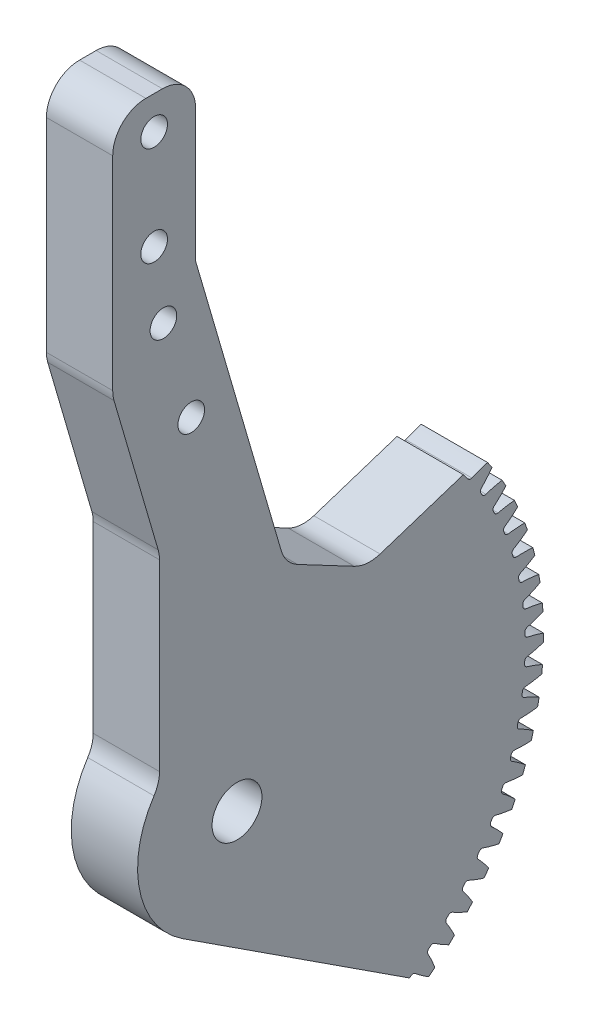
SolidWorks part; units mm, degrees
material "Delrin 2700 NC010, Low Viscosity Acetal Copolymer (SS)"
ref_plane "Front Plane" through (0, 0, 0) normal (0, 0, 1) x (1, 0, 0)
ref_plane "Top Plane" through (0, 0, 0) normal (0, 1, 0) x (1, 0, 0)
ref_plane "Right Plane" through (0, 0, 0) normal (1, 0, 0) x (0, 0, -1)
ref_plane "Plane1" through (-6.35, 0, 0) normal (-1, 0, 0) x (0, -1, 0)
sketch "Sketch1" plane through (-6.35, 0, 0) normal (-1, 0, 0) x (0, -1, 0)
  line L0 (-81.6791, 23.8125) -> (-120.65, 23.8125)
  line L1 (-127, 17.4625) -> (-127, 14.2875)
  line L2 (-120.65, 7.9375) -> (-95.25, 7.9375)
  line L3 (-95.25, 7.9375) -> (-38.9677, -8.4782)
  line L4 (-35.1315, -11.6072) -> (-29.3819, -22.4868)
  line L5 (-28.9579, -27.4191) -> (-34.0808, -43.1589)
  line L6 (44.0898, -32.8675) -> (15.9715, 10.3834)
  line L7 (-13.9936, 14.8476) -> (-49.1281, 14.8476)
  line L8 (-50.9061, 15.1016) -> (-79.9011, 23.5585)
  arc A0 (-120.65, 23.8125) -> (-127, 17.4625) centre (-120.65, 17.4625) ccw
  arc A1 (-127, 14.2875) -> (-120.65, 7.9375) centre (-120.65, 14.2875) ccw
  arc A2 (-38.9677, -8.4782) -> (-35.1315, -11.6072) centre (-40.7457, -14.5742) cw
  arc A3 (-29.3819, -22.4868) -> (-28.9579, -27.4191) centre (-34.9961, -25.4538) cw
  arc A4 (-34.0808, -43.1589) -> (-32.8888, -46.7381) centre (-31.0617, -44.1415) ccw
  arc A5 (-32.8888, -46.7381) -> (43.8649, -36.6333) centre (0, 0) ccw
  arc A6 (43.8649, -36.6333) -> (44.0898, -32.8675) centre (41.4279, -34.5981) ccw
  arc A7 (15.9715, 10.3834) -> (-10.4952, 15.8982) centre (0, 0) ccw
  arc A8 (-10.4952, 15.8982) -> (-13.9936, 14.8476) centre (-13.9936, 21.1976) cw
  arc A9 (-49.1281, 14.8476) -> (-50.9061, 15.1016) centre (-49.1281, 21.1976) cw
  arc A10 (-79.9011, 23.5585) -> (-81.6791, 23.8125) centre (-81.6791, 17.4625) ccw
  circle A11 centre (0, 0) radius 4.7752
extrude "Boss-Extrude1" add sketch "Sketch1" against normal blind 12.7
sketch "Sketch4" plane through (-6.35, 0, 0) normal (-1, 0, 0) x (0, 0, 1)
  line L0 (-43.1589, 34.0808) -> (-48.5319, 35.8296)
  line L1 (-32.8675, -44.0898) -> (-37.6049, -47.1697)
  line L2 (-32.8675, -44.0898) -> (10.3834, -15.9715) construction
  line L3 (-27.4191, 28.9579) -> (-43.1589, 34.0808) construction
  arc A1 (-36.6333, -43.8649) -> (-32.8675, -44.0898) centre (-34.5981, -41.4279) ccw construction
  arc A2 (-49.3346, 34.716) -> (-38.6685, -46.3018) centre (0, 0) ccw
  arc A3 (-48.5319, 35.8296) -> (-37.6049, -47.1697) centre (0, 0) ccw
  arc A4 (-46.7381, 32.8888) -> (-36.6333, -43.8649) centre (0, 0) ccw construction
  arc A5 (-43.1589, 34.0808) -> (-46.7381, 32.8888) centre (-44.1415, 31.0617) ccw construction
  arc A6 (-36.6333, -43.8649) -> (-32.8675, -44.0898) centre (-34.5981, -41.4279) ccw
  arc A7 (-46.7381, 32.8888) -> (-36.6333, -43.8649) centre (0, 0) ccw
  arc A8 (-43.1589, 34.0808) -> (-46.7381, 32.8888) centre (-44.1415, 31.0617) ccw
  dimension "D1" = 3.175
extrude "Boss-Extrude2" add sketch "Sketch4" against normal up to surface (12.7 mm away) up to face at (6.35, 0, -4.7752)
sketch "Sketch3" plane through (-6.35, 0, 0) normal (-1, 0, 0) x (0, 0, 1)
  line L0 (-27.4191, 28.9579) -> (-48.5319, 35.8296) construction
  line L1 (-37.6049, -47.1697) -> (10.3834, -15.9715) construction
  line L2 (-43.3632, 34.1473) -> (-48.5319, 35.8296)
  line L3 (-37.6049, -47.1697) -> (-33.0476, -44.2069)
  arc A117 (-33.3583, -43.973) -> (-33.0476, -44.2069) centre (0, 0) ccw
  arc A118 (-33.3583, -43.973) -> (-34.1326, -43.9889) centre (-33.7354, -44.47) ccw
  arc A119 (-36.7261, -45.8398) -> (-34.1326, -43.9889) centre (-48.5698, -26.5018) ccw
  arc A120 (-36.5809, -41.9749) -> (-37.8969, -44.8767) centre (-16.6379, -52.7688) ccw
  arc A121 (-36.5809, -41.9749) -> (-36.7146, -41.2121) centre (-37.1296, -41.678) ccw
  arc A122 (-37.0639, -40.8983) -> (-36.7146, -41.2121) centre (0, 0) ccw
  arc A123 (-37.0639, -40.8983) -> (-37.8366, -40.8467) centre (-37.4828, -41.3606) ccw
  arc A124 (-40.5815, -42.4645) -> (-37.8366, -40.8467) centre (-50.6947, -22.1679) ccw
  arc A125 (-40.1, -38.627) -> (-41.664, -41.403) centre (-21.1737, -51.1179) ccw
  arc A126 (-40.1, -38.627) -> (-40.1667, -37.8554) centre (-40.6208, -38.2833) ccw
  arc A127 (-40.4874, -37.5123) -> (-40.1667, -37.8554) centre (0, 0) ccw
  arc A128 (-40.4874, -37.5123) -> (-41.2526, -37.3936) centre (-40.945, -37.9363) ccw
  arc A129 (-44.1281, -38.766) -> (-41.2526, -37.3936) centre (-52.4339, -17.6652) ccw
  arc A130 (-43.314, -34.985) -> (-45.1139, -37.6142) centre (-25.5484, -49.078) ccw
  arc A131 (-43.314, -34.985) -> (-43.3132, -34.2106) centre (-43.8028, -34.5973) ccw
  arc A132 (-43.6027, -33.8409) -> (-43.3132, -34.2106) centre (0, 0) ccw
  arc A133 (-43.6027, -33.8409) -> (-44.3547, -33.6559) centre (-44.0956, -34.2234) ccw
  arc A134 (-47.3389, -34.7724) -> (-44.3547, -33.6559) centre (-53.774, -13.028) ccw
  arc A135 (-46.1983, -31.0769) -> (-48.2205, -33.5391) centre (-29.7286, -46.6645) ccw
  arc A136 (-46.1983, -31.0769) -> (-46.13, -30.3054) centre (-46.6515, -30.648) ccw
  arc A137 (-46.3862, -29.9119) -> (-46.13, -30.3054) centre (0, 0) ccw
  arc A138 (-46.3862, -29.9119) -> (-47.1192, -29.662) centre (-46.9105, -30.25) ccw
  arc A139 (-50.1894, -30.5143) -> (-47.1192, -29.662) centre (-54.7048, -8.2918) ccw
  arc A140 (-48.7311, -26.9321) -> (-50.9602, -29.2088) centre (-33.6825, -43.896) ccw
  arc A141 (-48.7311, -26.9321) -> (-48.5958, -26.1696) centre (-49.1451, -26.4654) ccw
  arc A142 (-48.8167, -25.7552) -> (-48.5958, -26.1696) centre (0, 0) ccw
  arc A143 (-48.8167, -25.7552) -> (-49.5251, -25.4424) centre (-49.3685, -26.0463) ccw
  arc A144 (-52.6579, -26.0239) -> (-49.5251, -25.4424) centre (-55.2193, -3.4924) ccw
  arc A145 (-50.8929, -22.5825) -> (-53.312, -24.6562) centre (-37.3802, -40.7933) ccw
  arc A146 (-50.8929, -22.5825) -> (-50.6917, -21.8346) centre (-51.2647, -22.0814) ccw
  arc A147 (-50.8756, -21.4025) -> (-50.6917, -21.8346) centre (0, 0) ccw
  arc A148 (-50.8756, -21.4025) -> (-51.5541, -21.0292) centre (-51.4507, -21.6445) ccw
  arc A149 (-54.7256, -21.3354) -> (-51.5541, -21.0292) centre (-55.3136, 1.3336) ccw
  arc A150 (-52.6675, -18.0609) -> (-55.258, -19.9159) centre (-40.7933, -37.3802) ccw
  arc A151 (-52.6675, -18.0609) -> (-52.4018, -17.3335) centre (-52.9941, -17.5294) ccw
  arc A152 (-52.5474, -16.887) -> (-52.4018, -17.3335) centre (0, 0) ccw
  arc A153 (-52.5474, -16.887) -> (-53.1908, -16.456) centre (-53.1414, -17.0779) ccw
  arc A154 (-56.3769, -16.4845) -> (-53.1908, -16.456) centre (-54.9868, 6.1494) ccw
  arc A155 (-54.0412, -13.4019) -> (-56.7835, -15.0241) centre (-43.896, -33.6825) ccw
  arc A156 (-54.0412, -13.4019) -> (-53.7131, -12.7004) centre (-54.3203, -12.844) ccw
  arc A157 (-53.8192, -12.2429) -> (-53.7131, -12.7004) centre (0, 0) ccw
  arc A158 (-53.8192, -12.2429) -> (-54.4226, -11.7574) centre (-54.4276, -12.3813) ccw
  arc A159 (-57.5991, -11.5082) -> (-54.4226, -11.7574) centre (-54.2416, 10.9184) ccw
  arc A160 (-55.0036, -8.6409) -> (-57.8769, -10.0179) centre (-46.6645, -29.7286) ccw
  arc A161 (-55.0036, -8.6409) -> (-54.6156, -7.9707) centre (-55.233, -8.0608) ccw
  arc A162 (-54.6815, -7.5057) -> (-54.6156, -7.9707) centre (0, 0) ccw
  arc A163 (-54.6815, -7.5057) -> (-55.2402, -6.9695) centre (-55.2996, -7.5905) ccw
  arc A164 (-58.3829, -6.4444) -> (-55.2402, -6.9695) centre (-53.0836, 15.6044) ccw
  arc A165 (-55.5474, -3.8142) -> (-58.5298, -4.9355) centre (-49.078, -25.5484) ccw
  arc A166 (-55.5474, -3.8142) -> (-55.1025, -3.1803) centre (-55.7254, -3.2162) ccw
  arc A167 (-55.1276, -2.7113) -> (-55.1025, -3.1803) centre (0, 0) ccw
  arc A168 (-55.1276, -2.7113) -> (-55.6375, -2.1284) centre (-55.7507, -2.742) ccw
  arc A169 (-58.7224, -1.3314) -> (-55.6375, -2.1284) centre (-51.5216, 20.1715) ccw
  arc A170 (-55.6684, 1.0416) -> (-58.7372, 0.1845) centre (-51.1179, -21.1737) ccw
  arc A171 (-55.6684, 1.0416) -> (-55.17, 1.6343) centre (-55.7936, 1.6528) ccw
  arc A172 (-55.1541, 2.1037) -> (-55.17, 1.6343) centre (0, 0) ccw
  arc A173 (-55.1541, 2.1037) -> (-55.6113, 2.7288) centre (-55.7775, 2.1275) ccw
  arc A174 (-58.615, 3.7916) -> (-55.6113, 2.7288) centre (-49.5675, 24.5852) ccw
  arc A175 (-55.3658, 5.8895) -> (-58.4976, 5.3031) centre (-52.7688, -16.6379) ccw
  arc A176 (-55.3658, 5.8895) -> (-54.8176, 6.4365) centre (-55.4372, 6.5093) ccw
  arc A177 (-54.7609, 6.9027) -> (-54.8176, 6.4365) centre (0, 0) ccw
  arc A178 (-54.7609, 6.9027) -> (-55.1618, 7.5652) centre (-55.3799, 6.9807) ccw
  arc A179 (-58.0615, 8.8858) -> (-55.1618, 7.5652) centre (-47.2361, 28.8117) ccw
  arc A180 (-54.6418, 10.6925) -> (-57.8128, 10.3813) centre (-54.0181, -11.9755) ccw
  arc A181 (-54.6418, 10.6925) -> (-54.048, 11.1897) centre (-54.659, 11.3162) ccw
  arc A182 (-53.9509, 11.6491) -> (-54.048, 11.1897) centre (0, 0) ccw
  arc A183 (-53.9509, 11.6491) -> (-54.2925, 12.3441) centre (-54.5607, 11.7808) ccw
  arc A184 (-57.0661, 13.9124) -> (-54.2925, 12.3441) centre (-44.5453, 32.819) ccw
  arc A185 (-53.502, 15.4142) -> (-56.688, 15.3805) centre (-54.8563, -7.222) ccw
  arc A186 (-53.502, 15.4142) -> (-52.8671, 15.8577) centre (-53.4647, 16.0369) ccw
  arc A187 (-52.7303, 16.3069) -> (-52.8671, 15.8577) centre (0, 0) ccw
  arc A188 (-52.7303, 16.3069) -> (-53.0101, 17.0291) centre (-53.3263, 16.4913) ccw
  arc A189 (-55.6364, 18.8331) -> (-53.0101, 17.0291) centre (-41.5154, 36.5765) ccw
  arc A190 (-51.9549, 20.0185) -> (-55.1318, 20.2627) centre (-55.277, -2.4134) ccw
  arc A191 (-51.9549, 20.0185) -> (-51.2839, 20.405) centre (-51.8636, 20.6357) ccw
  arc A192 (-51.1084, 20.8406) -> (-51.2839, 20.405) centre (0, 0) ccw
  arc A193 (-51.1084, 20.8406) -> (-51.3242, 21.5844) centre (-51.6861, 21.0762) ccw
  arc A194 (-53.7833, 23.6105) -> (-51.3242, 21.5844) centre (-38.1696, 40.0556) ccw
  arc A195 (-50.0125, 24.4705) -> (-53.156, 24.9907) centre (-55.277, 2.4134) ccw
  arc A196 (-50.0125, 24.4705) -> (-49.3103, 24.7971) centre (-49.8677, 25.0774) ccw
  arc A197 (-49.0975, 25.2157) -> (-49.3103, 24.7971) centre (0, 0) ccw
  arc A198 (-49.0975, 25.2157) -> (-49.2477, 25.9754) centre (-49.6525, 25.5007) ccw
  arc A199 (-51.5208, 28.2081) -> (-49.2477, 25.9754) centre (-34.5333, 43.2299) ccw
  arc A200 (-47.6895, 28.7363) -> (-50.7757, 29.5284) centre (-54.8563, 7.222) ccw
  arc A201 (-47.6895, 28.7363) -> (-46.9615, 29.0004) centre (-47.4923, 29.3282) ccw
  arc A202 (-46.713, 29.3989) -> (-46.9615, 29.0004) centre (0, 0) ccw
  arc A203 (-46.713, 29.3989) -> (-46.7964, 30.1688) centre (-47.241, 29.7312) ccw
  arc A204 (-48.8663, 32.5911) -> (-46.7964, 30.1688) centre (-30.6341, 46.0751) ccw
  arc A205 (-45.0035, 32.7833) -> (-48.0089, 33.8414) centre (-54.0181, 11.9755) ccw
  arc A206 (-45.0035, 32.7833) -> (-44.2552, 32.983) centre (-44.7554, 33.3558) ccw
  arc A207 (-43.3632, 34.1473) -> (-44.2552, 32.983) centre (0, 0) ccw
  arc A389 (-48.0089, 33.8414) -> (-48.8663, 32.5911) centre (0, 0) ccw
  arc A390 (-50.7757, 29.5284) -> (-51.5208, 28.2081) centre (0, 0) ccw
  arc A391 (-53.156, 24.9907) -> (-53.7833, 23.6105) centre (0, 0) ccw
  arc A392 (-55.1318, 20.2627) -> (-55.6364, 18.8331) centre (0, 0) ccw
  arc A393 (-56.688, 15.3805) -> (-57.0661, 13.9124) centre (0, 0) ccw
  arc A394 (-57.8128, 10.3813) -> (-58.0615, 8.8858) centre (0, 0) ccw
  arc A395 (-58.4976, 5.3031) -> (-58.615, 3.7916) centre (0, 0) ccw
  arc A396 (-58.7372, 0.1845) -> (-58.7224, -1.3314) centre (0, 0) ccw
  arc A397 (-58.5298, -4.9355) -> (-58.3829, -6.4444) centre (0, 0) ccw
  arc A398 (-57.8769, -10.0179) -> (-57.5991, -11.5082) centre (0, 0) ccw
  arc A399 (-56.7835, -15.0241) -> (-56.3769, -16.4845) centre (0, 0) ccw
  arc A400 (-55.258, -19.9159) -> (-54.7256, -21.3354) centre (0, 0) ccw
  arc A401 (-53.312, -24.6562) -> (-52.6579, -26.0239) centre (0, 0) ccw
  arc A402 (-50.9602, -29.2088) -> (-50.1894, -30.5143) centre (0, 0) ccw
  arc A403 (-48.2205, -33.5391) -> (-47.3389, -34.7724) centre (0, 0) ccw
  arc A404 (-45.1139, -37.6142) -> (-44.1281, -38.766) centre (0, 0) ccw
  arc A405 (-41.664, -41.403) -> (-40.5815, -42.4645) centre (0, 0) ccw
  arc A406 (-37.8969, -44.8767) -> (-36.7261, -45.8398) centre (0, 0) ccw
  arc A433 (-48.5319, 35.8296) -> (-37.6049, -47.1697) centre (0, 0) ccw construction
  arc A434 (-48.5319, 35.8296) -> (-37.6049, -47.1697) centre (0, 0) ccw
extrude "Cut-Extrude1" cut sketch "Sketch3" against normal through all
hole_wizard "#10 Clearance Hole1" positions "Sketch5" profile "Sketch6" hole size "#10" standard "ANSI Inch" end condition through all
sketch "Sketch5" plane through (-6.35, 0, 0) normal (-1, 0, 0) x (0, 0, 1)
  line L0 (15.875, 127) -> (15.875, 94.1161) construction
  line L1 (17.4625, 127) -> (14.2875, 127) construction
  line L3 (7.9375, 107.95) -> (23.8125, 107.95) construction
  line L4 (7.9375, 120.65) -> (7.9375, 95.25) construction
  line L5 (23.8125, 81.6791) -> (23.8125, 120.65) construction
  line L7 (3.592, 52.0028) -> (15.875, 94.1161) construction
  line L9 (7.9375, 95.25) -> (-8.4782, 38.9677) construction
  point P0 (15.875, 120.65)
  point P2 (15.875, 101.6)
  point P4 (14.097, 88.0201)
  point P6 (8.763, 69.7321)
  point P23 (15.875, 107.95)
  dimension "D1" = 7.9375
  dimension "D2" = 7.9375
  dimension "D3" = 19.05
  dimension "D4" = 6.35
  dimension "D5" = 19.05
  dimension "D6" = 6.35
sketch "Sketch6" plane through (-6.35, 120.65, 15.875) normal (0, 1, 0) x (0, 0, 1)
  line L0 (0, 0) -> (0, 12.7)
  line L1 (0, 12.7) -> (2.5527, 12.7)
  line L2 (2.5527, 12.7) -> (2.5527, 0)
  line L5 (2.5527, 0) -> (0, 0)
  line L11 (0, -6.35) -> (0, 107.95) construction
  dimension "Thru Hole Dia." = 5.1054
  dimension "Thru Hole Depth" = 12.7
equation "\"D2@Sketch5\"=\"D1@Sketch5\""
